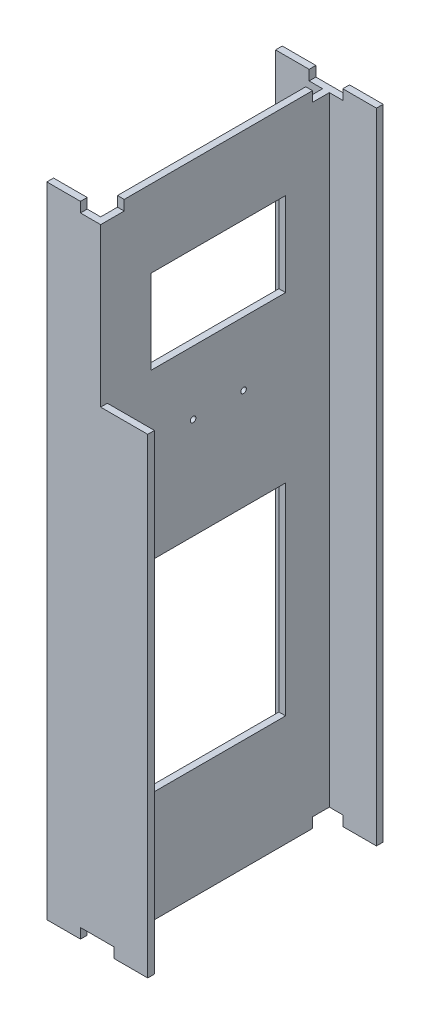
SolidWorks part; units mm, degrees
ref_plane "Front Plane" through (0, 0, 0) normal (0, 0, 1) x (1, 0, 0)
ref_plane "Top Plane" through (0, 0, 0) normal (0, 1, 0) x (1, 0, 0)
ref_plane "Right Plane" through (0, 0, 0) normal (1, 0, 0) x (0, 0, -1)
sketch "Sketch1" plane through (0, 0, 0) normal (0, 1, 0) x (1, 0, 0)
  line L0 (0, 0) -> (0, 66)
  line L2 (-16, 66) -> (-16, 68)
  line L3 (-16, 68) -> (14, 68)
  line L4 (14, 68) -> (14, 66)
  line L6 (-2, 66) -> (-2, 0)
  line L8 (14, 0) -> (14, -2)
  line L9 (14, -2) -> (-16, -2)
  line L10 (-16, -2) -> (-16, 0)
  line L12 (-16, 66) -> (-2, 66)
  line L13 (0, 66) -> (14, 66)
  line L14 (0, 0) -> (14, 0)
  line L15 (-2, 0) -> (-16, 0)
  dimension "D1" = 30
  dimension "D3" = 2
  dimension "D4" = 70
extrude "Boss-Extrude1" add sketch "Sketch1" along normal blind 95
sketch "Sketch3" plane through (0, 0, 0) normal (0, -1, 0) x (1, 0, 0)
  line L0 (48.883, 0) -> (-50.883, 0) construction
  line L1 (48.883, -66) -> (-50.883, -66) construction
  line L2 (-6, 5) -> (4, 5)
  line L3 (-6, 5) -> (-6, -5)
  line L4 (-6, -5) -> (4, -5)
  line L5 (4, 5) -> (4, -5)
  line L6 (-6, 5) -> (4, -5) construction
  line L7 (-6, -5) -> (4, 5) construction
  line L8 (-6, -61) -> (4, -61)
  line L9 (-6, -61) -> (-6, -71)
  line L10 (-6, -71) -> (4, -71)
  line L11 (4, -61) -> (4, -71)
  line L12 (-6, -61) -> (4, -71) construction
  line L13 (-6, -71) -> (4, -61) construction
  line L14 (-2, 0) -> (0, 0) construction
  line L15 (-2, -66) -> (0, -66) construction
  point P3 (-1, 0)
  point P9 (-1, -66)
  point P19 (-1, 0)
  point P24 (-1, -66)
  dimension "D1" = 10
  dimension "D2" = 10
extrude "Cut-Extrude2" cut sketch "Sketch3" against normal blind 3
mirror "Mirror2" about plane through (0, 95, 0) normal (0, -1, 0) of bodies 103
sketch "Sketch4" plane through (-2, 0, 0) normal (-1, 0, 0) x (0, 0, 1)
  line L0 (-53, 100) -> (-66, 100) construction
  line L1 (-13, 100) -> (0, 100) construction
  line L6 (-53, 167) -> (-53, 142)
  line L7 (-53, 142) -> (-13, 142)
  line L8 (-53, 167) -> (-13, 167)
  line L9 (-53, 167) -> (-53, 33) construction
  line L10 (-53, 33) -> (-13, 33)
  line L11 (-13, 167) -> (-13, 33) construction
  line L12 (-13, 142) -> (-13, 167)
  line L13 (-53, 33) -> (-53, 93)
  line L14 (-53, 93) -> (-13, 93)
  line L15 (-13, 93) -> (-13, 33)
  line L23 (-61, 0) -> (-5, 0)
  line L24 (-5, 0) -> (-5, 3)
  line L25 (-5, 3) -> (0, 3)
  line L26 (0, 3) -> (0, 187)
  line L27 (0, 187) -> (-5, 187)
  line L28 (-5, 187) -> (-5, 190)
  line L29 (-5, 190) -> (-61, 190)
  line L30 (-61, 190) -> (-61, 187)
  line L31 (-61, 187) -> (-66, 187)
  line L32 (-66, 187) -> (-66, 3)
  line L33 (-66, 3) -> (-61, 3)
  line L34 (-61, 3) -> (-61, 0)
  line L35 (-61, 0) -> (-5, 0) construction
  line L36 (-5, 0) -> (-5, 3) construction
  line L37 (-5, 3) -> (0, 3) construction
  line L38 (0, 3) -> (0, 187) construction
  line L39 (0, 187) -> (-5, 187) construction
  line L40 (-5, 187) -> (-5, 190) construction
  line L41 (-5, 190) -> (-61, 190) construction
  line L42 (-61, 190) -> (-61, 187) construction
  line L43 (-61, 187) -> (-66, 187) construction
  line L44 (-66, 187) -> (-66, 3) construction
  line L45 (-66, 3) -> (-61, 3) construction
  line L46 (-61, 3) -> (-61, 0) construction
  dimension "D1" = 30
  dimension "D3" = 40
  dimension "D2" = 20
  dimension "D5" = 60
  dimension "D6" = 25
  dimension "D4" = 0
extrude "Cut-Extrude8" cut sketch "Sketch4" against normal blind 2
sketch "Sketch5" plane through (0, 0, 0) normal (0, 0, -1) x (-1, 0, 0)
  line L0 (0, 187) -> (0, 3) construction
  line L1 (-14, 190) -> (0, 190)
  line L2 (-14, 190) -> (-14, 140)
  line L3 (-14, 140) -> (0, 140)
  line L4 (0, 190) -> (0, 140)
  dimension "D1" = 50
extrude "Cut-Extrude9" cut sketch "Sketch5" against normal up to surface (2 mm away) up to face at (-1, 95, 2)
sketch "Sketch6" plane through (-2, 0, 0) normal (-1, 0, 0) x (0, 0, 1)
  circle A0 centre (-25.5, 123.0748) radius 0.825 construction
  circle A1 centre (-40.5, 123.0748) radius 0.825 construction
  circle A2 centre (-25.5, 123.0748) radius 0.825
  circle A3 centre (-40.5, 123.0748) radius 0.825
extrude "Cut-Extrude10" cut sketch "Sketch6" against normal through all
equation "\"w_BeamWidth\"=30"
equation "\"D1@Sketch1\"=\"w_BeamWidth\""
equation "\"TBeam\"=2"
equation "\"D2@Sketch1\"=\"TBeam\""
equation "\"D3@Sketch1\"=\"TBeam\""
equation "\"BeamLength\"= 70"
equation "\"D4@Sketch1\"=\"BeamLength\""
equation "\"BeamHeight\"= 190"
equation "\"D1@Boss-Extrude1\"=\"BeamHeight\"/2"
equation "\"HoleHeightInBeam\"=160"
equation "\"HoleSizeInBeam\"=40"
equation "\"D3@Sketch4\"=\"HoleSizeInBeam\""
equation "\"D1@Cut-Extrude8\" = \"TBeam\""
equation "\"HoleHieght1\"=60"
equation "\"D5@Sketch4\"=\"HoleHieght1\""
equation "\"HoleHieght2\"=25"
equation "\"D6@Sketch4\"=\"HoleHieght2\""
equation "\"CounterWeightCutoutHeight\"=50"
equation "\"D1@Sketch5\"=\"CounterWeightCutoutHeight\""
